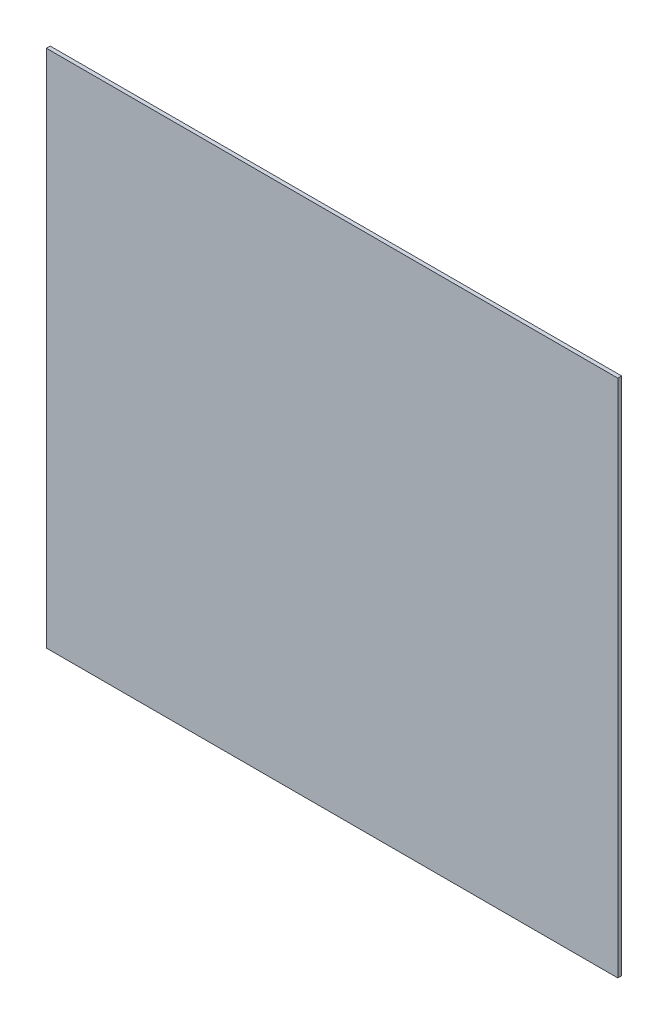
SolidWorks part; units mm, degrees
ref_plane "Front Plane" through (0, 0, 0) normal (0, 0, 1) x (1, 0, 0)
ref_plane "Top Plane" through (0, 0, 0) normal (0, 1, 0) x (1, 0, 0)
ref_plane "Right Plane" through (0, 0, 0) normal (1, 0, 0) x (0, 0, -1)
sketch "Sketch1" plane through (0, 0, 0) normal (0, 0, 1) x (1, 0, 0)
  line L1 (0, 5) -> (11, 5)
  line L2 (0, 5) -> (0, -5)
  line L3 (0, -5) -> (11, -5)
  line L4 (11, 5) -> (11, -5)
  point P6 (0, 0)
  dimension "D1" = 10
  dimension "D2" = 11
extrude "Boss-Extrude1" add sketch "Sketch1" along normal blind 0.0737
